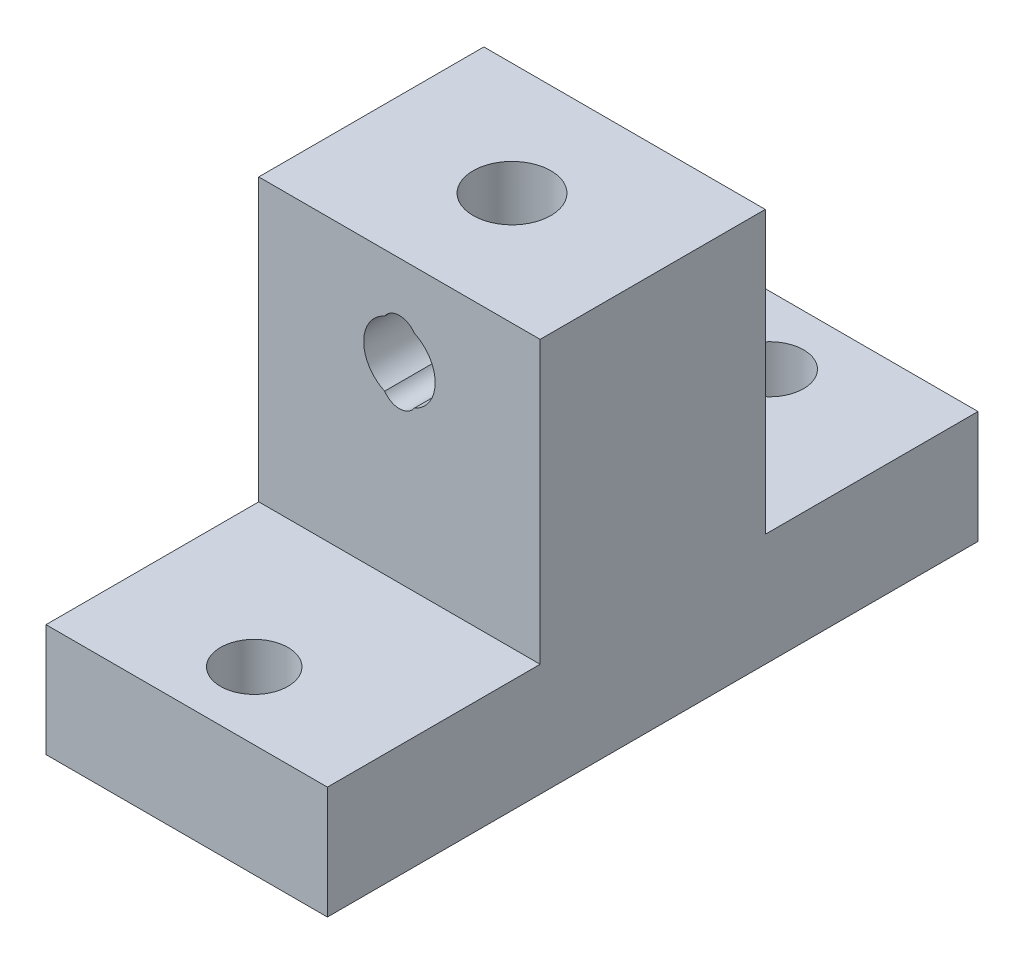
SolidWorks part; units mm, degrees
ref_plane "Front Plane" through (0, 0, 0) normal (0, 0, 1) x (1, 0, 0)
ref_plane "Top Plane" through (0, 0, 0) normal (0, 1, 0) x (1, 0, 0)
ref_plane "Right Plane" through (0, 0, 0) normal (1, 0, 0) x (0, 0, -1)
sketch "Sketch1" plane through (0, 0, 0) normal (0, 1, 0) x (1, 0, 0)
  line L1 (-6.25, -14.45) -> (6.25, -14.45)
  line L2 (-6.25, -14.45) -> (-6.25, 14.45)
  line L3 (-6.25, 14.45) -> (6.25, 14.45)
  line L4 (6.25, -14.45) -> (6.25, 14.45)
  line L5 (-6.25, -14.45) -> (6.25, 14.45) construction
  line L6 (-6.25, 14.45) -> (6.25, -14.45) construction
  point P0 (0, 0)
  dimension "D1" = 12.5
  dimension "D2" = 28.9
extrude "Extrude1" add sketch "Sketch1" along normal blind 5
sketch "Sketch2" plane through (0, 5, 0) normal (0, 1, 0) x (-1, 0, 0)
  line L0 (0, -15.9522) -> (0, 16.2084) construction
  line L1 (11.3788, 0) -> (-13.9765, 0) construction
hole_wizard "Ø3.0 (3) Diameter Hole1" positions "3DSketch2" profile "Sketch4" hole size "Ø3.0" standard "Ansi Metric" end condition through all
sketch3d "3DSketch2"
  line L0 (0, 5, -15.9522) -> (0, 5, 16.2084) construction
  line L1 (-11.3788, 5, 0) -> (13.9765, 5, 0) construction
  point P0 (0, 5, -11.45)
  point P4 (0, 5, 11.45)
  dimension "D1" = 11.45
  dimension "D2" = 11.45
sketch "Sketch4" plane through (0, 5, -11.45) normal (1, 0, 0) x (0, 0, 1)
  line L0 (0, 0) -> (0, 5)
  line L1 (0, 5) -> (1.5, 5)
  line L2 (1.5, 5) -> (1.5, 0)
  line L5 (1.5, 0) -> (0, 0)
  line L11 (0, -6.35) -> (0, 107.95) construction
  dimension "Thru Hole Dia." = 3
  dimension "Thru Hole Depth" = 5
sketch "Sketch5" plane through (0, 5, 0) normal (0, 1, 0) x (1, 0, 0)
  line L0 (6.25, -14.45) -> (6.25, 14.45) construction
  line L1 (-6.25, -5) -> (6.25, -5)
  line L2 (-6.25, -5) -> (-6.25, 5)
  line L3 (-6.25, 5) -> (6.25, 5)
  line L4 (6.25, -5) -> (6.25, 5)
  line L5 (-6.25, -5) -> (6.25, 5) construction
  line L6 (-6.25, 5) -> (6.25, -5) construction
  point P0 (0, 0)
  dimension "D1" = 10
extrude "Extrude3" add sketch "Sketch5" along normal blind 12.5
sketch "Sketch6" plane through (0, 0, -5) normal (0, 0, -1) x (-1, 0, 0)
  line L0 (0, 19.7959) -> (0, -2.2207) construction
hole_wizard "1/8 (0.125) Diameter Hole1" positions "3DSketch3" profile "Sketch7" hole size "1/8" standard "Ansi Inch" end condition through all
sketch3d "3DSketch3"
  line L0 (0, 19.7959, -5) -> (0, -2.2207, -5) construction
  line L1 (6.25, 17.5, -5) -> (-6.25, 17.5, -5) construction
  point P0 (0, 13.5, -5)
  dimension "D1" = 4
sketch "Sketch7" plane through (0, 13.5, -5) normal (1, 0, 0) x (0, 1, 0)
  line L0 (0, 0) -> (0, 19.45)
  line L1 (0, 19.45) -> (1.5875, 19.45)
  line L2 (1.5875, 19.45) -> (1.5875, 0)
  line L5 (1.5875, 0) -> (0, 0)
  line L11 (0, -6.35) -> (0, 107.95) construction
  dimension "Thru Hole Dia." = 3.175
  dimension "Thru Hole Depth" = 19.45
hole_wizard "#8-32 Tapped Hole1" positions "3DSketch5" profile "Sketch9" tap size "#8-32" standard "Ansi Inch" end condition through all
sketch3d "3DSketch5"
  line L0 (-6.25, 17.5, -5) -> (-6.25, 17.5, 5) construction
  line L1 (-6.25, 17.5, 5) -> (6.25, 17.5, 5) construction
  point P0 (0, 0, 0)
  point P4 (0, 17.5, 0)
  dimension "D1" = 6.25
  dimension "D2" = 5
sketch "Sketch9" plane through (0, 17.5, 0) normal (1, 0, 0) x (0, 0, 1)
  line L0 (0, 0) -> (0, 17.5)
  line L1 (0, 17.5) -> (1.7272, 17.5)
  line L2 (1.7272, 17.5) -> (1.7272, 0)
  line L5 (1.7272, 0) -> (0, 0)
  line L11 (0, -6.35) -> (0, 107.95) construction
  dimension "Thread Major Dia." = 3.4544
  dimension "Thru Tap Drill Depth" = 17.5
hole_wizard "1/16 (0.0625) Diameter Hole2" positions "3DSketch6" profile "Sketch10" hole size "1/16" standard "Ansi Inch"
sketch3d "3DSketch6"
  line L0 (0, 19.7959, -5) -> (0, -2.2207, -5) construction
  line L1 (6.25, 17.5, -5) -> (-6.25, 17.5, -5) construction
  point P0 (0, 14.5, -5)
  point P4 (0, 12.5, -5)
  dimension "D1" = 3
  dimension "D2" = 5
sketch "Sketch10" plane through (0, 14.5, -5) normal (1, 0, 0) x (0, 1, 0)
  line L0 (0, 0) -> (0, 19.9269)
  line L1 (0, 19.9269) -> (0.7937, 19.45)
  line L2 (0.7937, 19.45) -> (0.7937, 0)
  line L5 (0.7937, 0) -> (0, 0)
  line L10 (0, 19.9269) -> (-0.7938, 19.45) construction
  line L11 (0, -6.35) -> (0, 107.95) construction
  dimension "Hole Dia." = 1.5875
  dimension "Hole Depth" = 19.45
  dimension "Drill Angle" = 118
